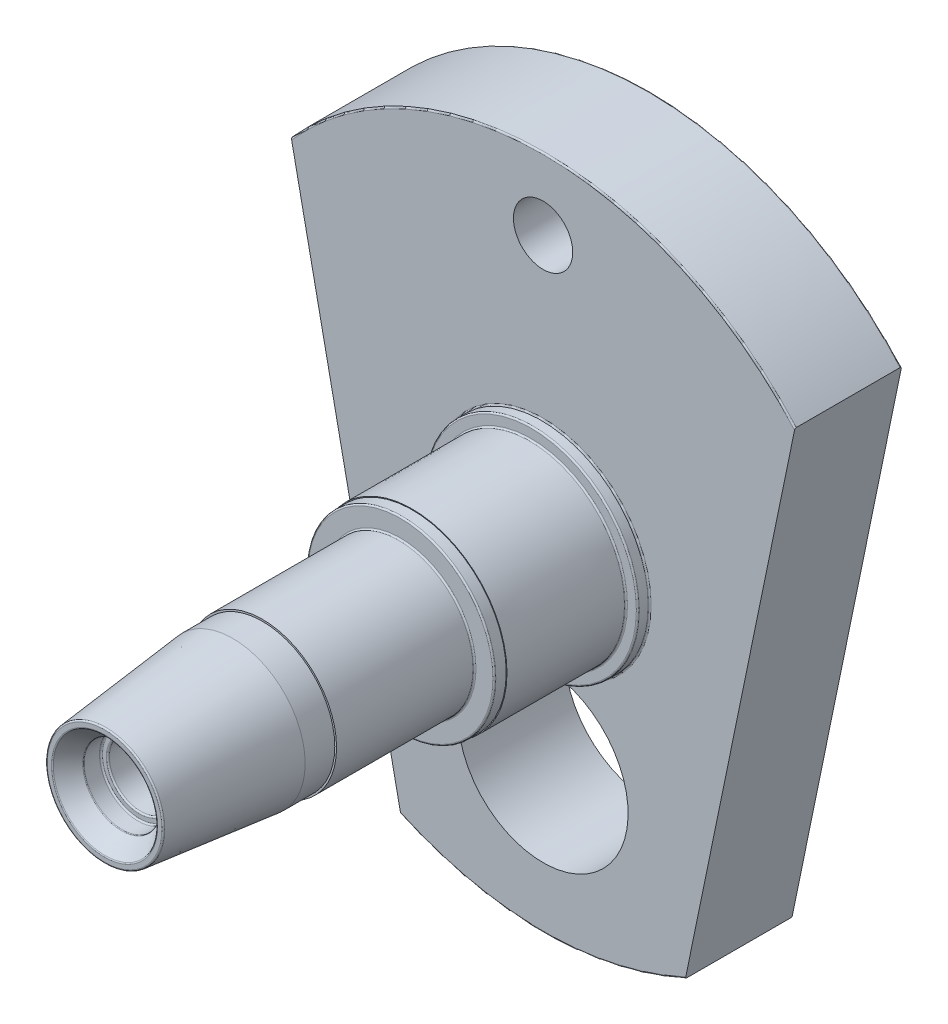
SolidWorks part; units mm, degrees
ref_plane "Front Plane" through (0, 0, 0) normal (0, 0, 1) x (1, 0, 0)
ref_plane "Top Plane" through (0, 0, 0) normal (0, 1, 0) x (1, 0, 0)
ref_plane "Right Plane" through (0, 0, 0) normal (1, 0, 0) x (0, 0, -1)
sketch "Sketch1" plane through (0, 0, 0) normal (1, 0, 0) x (0, 0, -1)
  line L0 (0, 0) -> (92, 0) construction
  line L2 (92, 6.305) -> (91, 5.305)
  line L3 (91.75, 57) -> (74.25, 57)
  line L4 (74, 56.75) -> (74, 18.2405)
  line L5 (2.8663, 6.5253) -> (0.0931, 8.7599)
  line L6 (49.93, 15.6) -> (49.93, 12.75)
  line L7 (92, 56.75) -> (92, 6.305)
  line L8 (72, 16.2404) -> (72, 17.7405)
  line L9 (72.25, 17.9905) -> (73.75, 17.9905)
  line L12 (49.68, 12.5) -> (26.65, 12.5)
  line L13 (51.93, 15.9809) -> (71.7501, 15.9904)
  line L14 (51.93, 15.85) -> (50.18, 15.85)
  line L15 (26.65, 12.5) -> (26.65, 12.2)
  line L16 (26.65, 12.2) -> (21.65, 12.2)
  line L17 (51.93, 15.85) -> (51.93, 15.9809)
  line L18 (3.0232, 6.47) -> (5.62, 6.47)
  line L19 (0.2236, 9.9238) -> (21.65, 12.2)
  line L20 (0, 9.6752) -> (0, 8.9545)
  line L22 (5.87, 6.22) -> (5.87, 5.555)
  line L23 (6.12, 5.305) -> (91, 5.305)
  arc A0 (50.18, 15.85) -> (49.93, 15.6) centre (50.18, 15.6) ccw
  arc A1 (5.87, 5.555) -> (6.12, 5.305) centre (6.12, 5.555) ccw
  arc A2 (5.62, 6.47) -> (5.87, 6.22) centre (5.62, 6.22) cw
  arc A3 (0, 9.6752) -> (0.2236, 9.9238) centre (0.25, 9.6752) cw
  arc A4 (2.8663, 6.5253) -> (3.0232, 6.47) centre (3.0232, 6.72) ccw
  arc A5 (0, 8.9545) -> (0.0931, 8.7599) centre (0.25, 8.9545) ccw
  arc A6 (49.68, 12.5) -> (49.93, 12.75) centre (49.68, 12.75) ccw
  arc A7 (71.7501, 15.9904) -> (72, 16.2404) centre (71.75, 16.2404) ccw
  arc A8 (72, 17.7405) -> (72.25, 17.9905) centre (72.25, 17.7405) cw
  arc A9 (73.75, 17.9905) -> (74, 18.2405) centre (73.75, 18.2405) ccw
  arc A10 (92, 56.75) -> (91.75, 57) centre (91.75, 56.75) ccw
  arc A11 (74.25, 57) -> (74, 56.75) centre (74.25, 56.75) ccw
  dimension "D1" = 0.25
  dimension "D2" = 0.25
revolve "Revolve1" add sketch "Sketch1" angle 360 about L0
sketch "Sketch2" plane through (0, 0, -92) normal (0, 0, -1) x (-1, 0, 0)
  line L1 (42.5003, 37.9833) -> (24.0164, -51.6935)
  line L3 (0, 39.95) -> (0, 44.95) construction
  line L4 (-42.5003, 37.9833) -> (-24.0164, -51.6935)
  arc A0 (-24.0164, -51.6935) -> (24.0164, -51.6935) centre (0, 0) ccw
  circle A1 centre (0, -32.4) radius 14.35
  arc A2 (42.5003, 37.9833) -> (-42.5003, 37.9833) centre (0, 0) ccw
  circle A6 centre (0, 44.95) radius 5
extrude "Cut-Extrude1" cut sketch "Sketch2" against normal blind 30 flip side to cut
